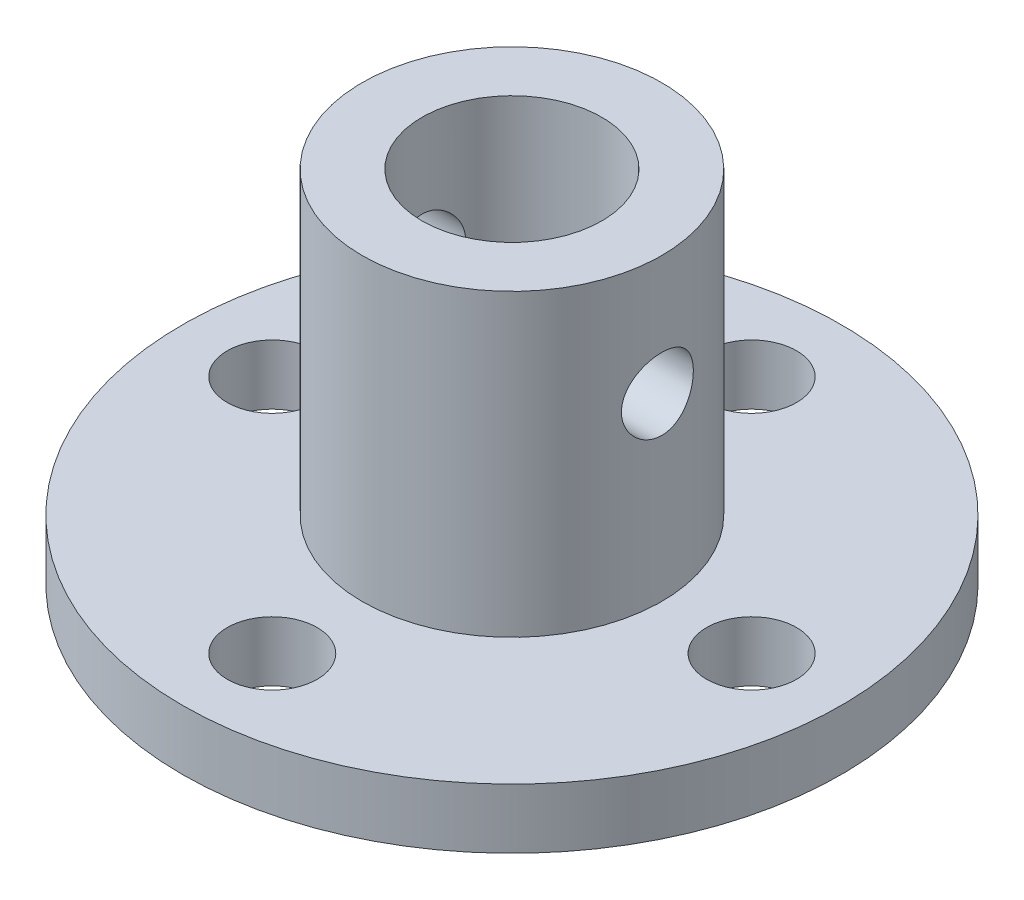
SolidWorks part; units mm, degrees
ref_plane "前视基准面" through (0, 0, 0) normal (0, 0, 1) x (1, 0, 0)
ref_plane "上视基准面" through (0, 0, 0) normal (0, 1, 0) x (1, 0, 0)
ref_plane "右视基准面" through (0, 0, 0) normal (1, 0, 0) x (0, 0, -1)
sketch "草图1" plane through (0, 0, 0) normal (0, 1, 0) x (1, 0, 0)
  circle A0 centre (0, 0) radius 11
extrude "凸台-拉伸1" add sketch "草图1" along normal blind 2
sketch "草图2" plane through (0, 2, 0) normal (0, 1, 0) x (1, 0, 0)
  circle A0 centre (0, 0) radius 5
extrude "凸台-拉伸2" add sketch "草图2" along normal blind 10
sketch "草图3" plane through (0, 12, 0) normal (0, 1, 0) x (1, 0, 0)
  circle A0 centre (0, 0) radius 3
extrude "切除-拉伸1" cut sketch "草图3" against normal through all
sketch "草图4" plane through (0, 2, 0) normal (0, 1, 0) x (1, 0, 0)
  circle A0 centre (0, 8) radius 1.5
  circle A1 centre (0, 0) radius 11 construction
  circle A2 centre (8, 0) radius 1.5
  circle A3 centre (0, -8) radius 1.5
  circle A4 centre (-8, 0) radius 1.5
  point P12 (0, 0)
  dimension "D1" = 8
  dimension "D2" = 4
extrude "切除-拉伸2" cut sketch "草图4" against normal blind 10
sketch "草图5" plane through (0, 0, 0) normal (1, 0, 0) x (0, 0, -1)
  line L0 (5, 12) -> (-5, 12) construction
  circle A0 centre (0, 8) radius 1.2
  dimension "D1" = 4
extrude "切除-拉伸3" cut sketch "草图5" against normal through all and the other way through all
